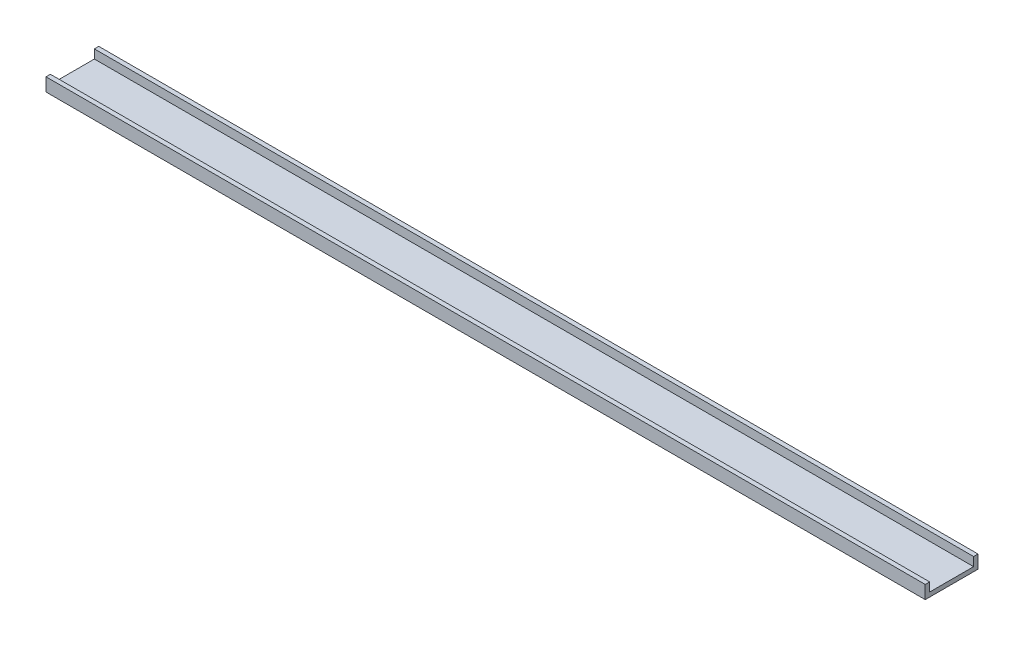
SolidWorks part; units mm, degrees
ref_plane "前视基准面" through (0, 0, 0) normal (0, 0, 1) x (1, 0, 0)
ref_plane "上视基准面" through (0, 0, 0) normal (0, 1, 0) x (1, 0, 0)
ref_plane "右视基准面" through (0, 0, 0) normal (1, 0, 0) x (0, 0, -1)
sketch "草图1" plane through (0, 0, 0) normal (0, 1, 0) x (1, 0, 0)
  line L1 (-255.3191, 84.2199) -> (744.6809, 84.2199)
  line L2 (-255.3191, 84.2199) -> (-255.3191, 24.2199)
  line L3 (-255.3191, 24.2199) -> (744.6809, 24.2199)
  line L4 (744.6809, 84.2199) -> (744.6809, 24.2199)
  dimension "D1" = 1000
  dimension "D2" = 60
extrude "凸台-拉伸1" add sketch "草图1" along normal blind 15
sketch "草图2" plane through (0, 15, 0) normal (0, 1, 0) x (1, 0, 0)
  line L0 (-255.3191, 84.2199) -> (-255.3191, 24.2199) construction
  line L1 (-255.3191, 79.2199) -> (744.6809, 79.2199)
  line L2 (-255.3191, 79.2199) -> (-255.3191, 29.2199)
  line L3 (-255.3191, 29.2199) -> (744.6809, 29.2199)
  line L4 (744.6809, 79.2199) -> (744.6809, 29.2199)
  line L5 (744.6809, 24.2199) -> (744.6809, 84.2199) construction
  line L6 (744.6809, 84.2199) -> (-255.3191, 84.2199) construction
  line L7 (-255.3191, 24.2199) -> (744.6809, 24.2199) construction
  dimension "D1" = 5
  dimension "D2" = 5
extrude "切除-拉伸1" cut sketch "草图2" against normal blind 10
scale "缩放比例1" scale about origin uniform scaling yes scale factor 1.7
